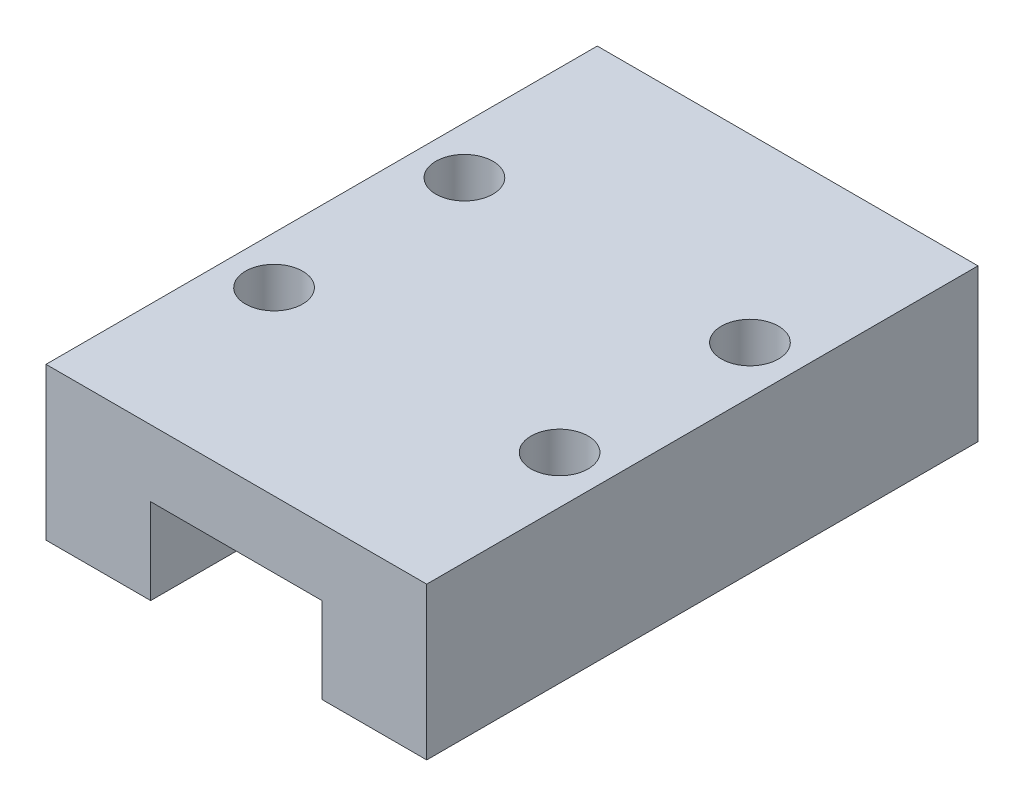
SolidWorks part; units mm, degrees
ref_plane "前视基准面" through (0, 0, 0) normal (0, 0, 1) x (1, 0, 0)
ref_plane "上视基准面" through (0, 0, 0) normal (0, 1, 0) x (1, 0, 0)
ref_plane "右视基准面" through (0, 0, 0) normal (1, 0, 0) x (0, 0, -1)
other "Configuration Table"
sketch "草图1" plane through (0, 0, 0) normal (0, 0, 1) x (1, 0, 0)
  line L0 (5.5, 0) -> (5.5, 4.5)
  line L1 (0, 0) -> (5.5, 0)
  line L2 (0, 0) -> (0, 8)
  line L3 (0, 8) -> (20, 8)
  line L4 (20, 0) -> (20, 8)
  line L5 (5.5, 4.5) -> (14.5, 4.5)
  line L6 (14.5, 4.5) -> (14.5, 0)
  line L7 (14.5, 0) -> (20, 0)
  dimension "D1" = 20
  dimension "D2" = 8
  dimension "D3" = 4.5
  dimension "D4" = 9
  dimension "D5" = 5.5
extrude "凸台-拉伸1" add sketch "草图1" along normal blind 28.96
sketch "草图2" plane through (0, 8, 0) normal (0, 1, 0) x (1, 0, 0)
  line L0 (20, 0) -> (0, 0) construction
  line L1 (2.5, -9.48) -> (17.5, -9.48) construction
  line L2 (2.5, -9.48) -> (2.5, -19.48) construction
  line L3 (2.5, -19.48) -> (17.5, -19.48) construction
  line L4 (17.5, -9.48) -> (17.5, -19.48) construction
  line L5 (20, -28.96) -> (20, 0) construction
  circle A0 centre (17.5, -9.48) radius 1.5
  circle A1 centre (17.5, -19.48) radius 1.5
  circle A2 centre (2.5, -19.48) radius 1.5
  circle A3 centre (2.5, -9.48) radius 1.5
  dimension "D5" = 3
  dimension "D1" = 15
  dimension "D2" = 10
  dimension "D3" = 9.48
  dimension "D4" = 2.5
extrude "切除-拉伸1" cut sketch "草图2" against normal blind 28.96
